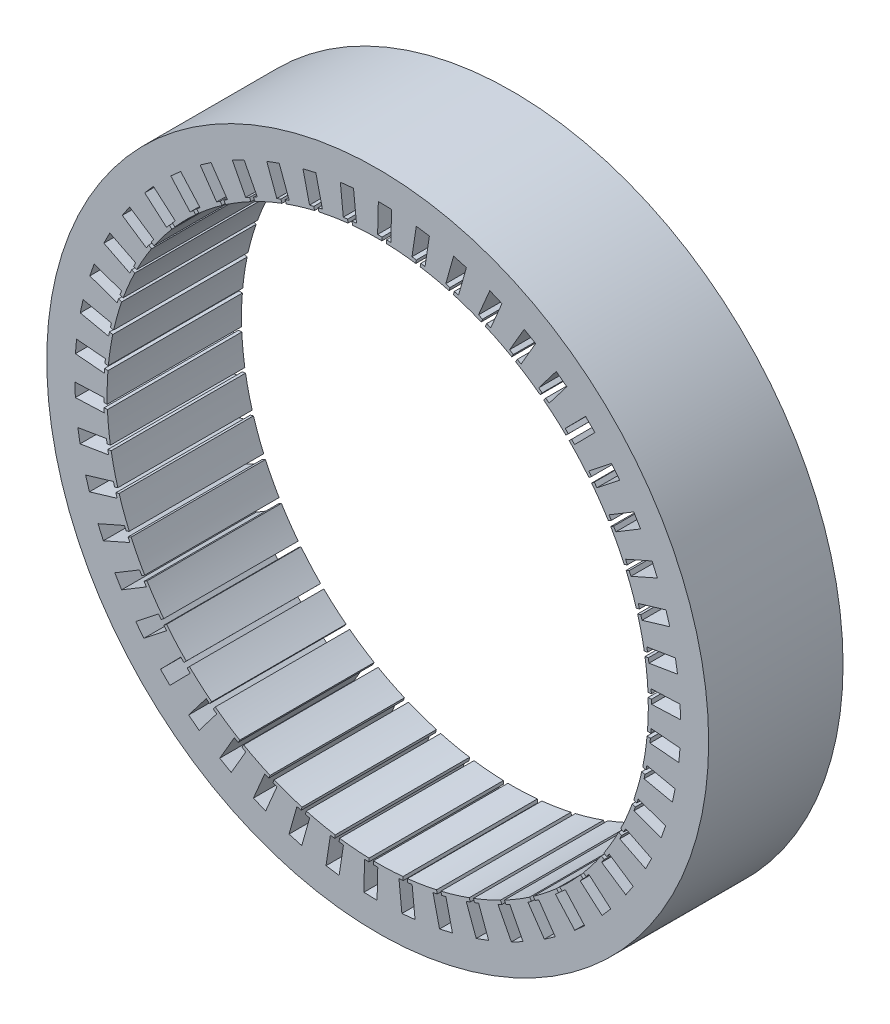
SolidWorks part; units mm, degrees
ref_plane "Спереди" through (0, 0, 0) normal (0, 0, 1) x (1, 0, 0)
ref_plane "Сверху" through (0, 0, 0) normal (0, 1, 0) x (1, 0, 0)
ref_plane "Справа" through (0, 0, 0) normal (1, 0, 0) x (0, 0, -1)
sketch "Эскиз1" plane through (0, 0, 0) normal (0, 0, 1) x (1, 0, 0)
  circle A0 centre (0, 0) radius 73.8769
  circle A1 centre (0, 0) radius 60.4
extrude "Rotor_stack" add sketch "Эскиз1" along normal blind 30 from offset 15
sketch "Эскиз2" plane through (0, 0, 0) normal (0, 0, 1) x (1, 0, 0)
  line L0 (59.5722, 1.8215) -> (61.1116, 1.8815)
  line L1 (61.1116, 1.8815) -> (61.1496, 0.9053)
  line L2 (61.1496, 0.9053) -> (67.6062, 1.1569)
  line L3 (67.6062, 1.1569) -> (67.4912, 4.1085)
  line L4 (67.4912, 4.1085) -> (61.0346, 3.8569)
  line L5 (61.0346, 3.8569) -> (61.0726, 2.8807)
  line L6 (61.0726, 2.8807) -> (59.5332, 2.8207)
  line L7 (59.5332, 2.8207) -> (59.5722, 1.8215)
  line L8 (58.8741, 9.2735) -> (60.3939, 9.5259)
  line L9 (60.3939, 9.5259) -> (60.554, 8.5622)
  line L10 (60.554, 8.5622) -> (66.9281, 9.6211)
  line L11 (66.9281, 9.6211) -> (66.4441, 12.535)
  line L12 (66.4441, 12.535) -> (60.0699, 11.4761)
  line L13 (60.0699, 11.4761) -> (60.23, 10.5124)
  line L14 (60.23, 10.5124) -> (58.7102, 10.26)
  line L15 (58.7102, 10.26) -> (58.8741, 9.2735)
  line L16 (57.2476, 16.5792) -> (58.7237, 17.0202)
  line L17 (58.7237, 17.0202) -> (59.0033, 16.0841)
  line L18 (59.0033, 16.0841) -> (65.1945, 17.9336)
  line L19 (65.1945, 17.9336) -> (64.3491, 20.7638)
  line L20 (64.3491, 20.7638) -> (58.1579, 18.9144)
  line L21 (58.1579, 18.9144) -> (58.4375, 17.9783)
  line L22 (58.4375, 17.9783) -> (56.9614, 17.5374)
  line L23 (56.9614, 17.5374) -> (57.2476, 16.5792)
  line L24 (54.7183, 23.6235) -> (56.1275, 24.246)
  line L25 (56.1275, 24.246) -> (56.5222, 23.3524)
  line L26 (56.5222, 23.3524) -> (62.4328, 25.9632)
  line L27 (62.4328, 25.9632) -> (61.2393, 28.6652)
  line L28 (61.2393, 28.6652) -> (55.3287, 26.0544)
  line L29 (55.3287, 26.0544) -> (55.7234, 25.1607)
  line L30 (55.7234, 25.1607) -> (54.3142, 24.5383)
  line L31 (54.3142, 24.5383) -> (54.7183, 23.6235)
  line L32 (51.326, 30.2953) -> (52.6461, 31.0895)
  line L33 (52.6461, 31.0895) -> (53.1497, 30.2524)
  line L34 (53.1497, 30.2524) -> (58.6864, 33.5834)
  line L35 (58.6864, 33.5834) -> (57.1637, 36.1145)
  line L36 (57.1637, 36.1145) -> (51.6269, 32.7834)
  line L37 (51.6269, 32.7834) -> (52.1305, 31.9463)
  line L38 (52.1305, 31.9463) -> (50.8105, 31.1522)
  line L39 (50.8105, 31.1522) -> (51.326, 30.2953)
  line L40 (47.1243, 36.4892) -> (48.3344, 37.4426)
  line L41 (48.3344, 37.4426) -> (48.9389, 36.6752)
  line L42 (48.9389, 36.6752) -> (54.0146, 40.6739)
  line L43 (54.0146, 40.6739) -> (52.1866, 42.9942)
  line L44 (52.1866, 42.9942) -> (47.111, 38.9955)
  line L45 (47.111, 38.9955) -> (47.7155, 38.2281)
  line L46 (47.7155, 38.2281) -> (46.5054, 37.2748)
  line L47 (46.5054, 37.2748) -> (47.1243, 36.4892)
  line L48 (42.1794, 42.1077) -> (43.2604, 43.2053)
  line L49 (43.2604, 43.2053) -> (43.9564, 42.5197)
  line L50 (43.9564, 42.5197) -> (48.4908, 47.123)
  line L51 (48.4908, 47.123) -> (46.3865, 49.1959)
  line L52 (46.3865, 49.1959) -> (41.8521, 44.5926)
  line L53 (41.8521, 44.5926) -> (42.548, 43.907)
  line L54 (42.548, 43.907) -> (41.4669, 42.8095)
  line L55 (41.4669, 42.8095) -> (42.1794, 42.1077)
  line L56 (36.5693, 47.0622) -> (37.5043, 48.2866)
  line L57 (37.5043, 48.2866) -> (38.2807, 47.6936)
  line L58 (38.2807, 47.6936) -> (42.2024, 52.829)
  line L59 (42.2024, 52.829) -> (39.8548, 54.6217)
  line L60 (39.8548, 54.6217) -> (35.9331, 49.4864)
  line L61 (35.9331, 49.4864) -> (36.7095, 48.8935)
  line L62 (36.7095, 48.8935) -> (35.7745, 47.6691)
  line L63 (35.7745, 47.6691) -> (36.5693, 47.0622)
  line L64 (30.3824, 51.2744) -> (31.1566, 52.6063)
  line L65 (31.1566, 52.6063) -> (32.0012, 52.1154)
  line L66 (32.0012, 52.1154) -> (35.2484, 57.7018)
  line L67 (35.2484, 57.7018) -> (32.6946, 59.1862)
  line L68 (32.6946, 59.1862) -> (29.4475, 53.5998)
  line L69 (29.4475, 53.5998) -> (30.2921, 53.1089)
  line L70 (30.2921, 53.1089) -> (29.5179, 51.777)
  line L71 (29.5179, 51.777) -> (30.3824, 51.2744)
  line L72 (23.7165, 54.678) -> (24.3176, 56.0965)
  line L73 (24.3176, 56.0965) -> (25.2171, 55.7153)
  line L74 (25.2171, 55.7153) -> (27.7385, 61.6645)
  line L75 (27.7385, 61.6645) -> (25.0188, 62.8172)
  line L76 (25.0188, 62.8172) -> (22.4974, 56.8679)
  line L77 (22.4974, 56.8679) -> (23.3969, 56.4867)
  line L78 (23.3969, 56.4867) -> (22.7958, 55.0683)
  line L79 (22.7958, 55.0683) -> (23.7165, 54.678)
  line L80 (16.6765, 57.2194) -> (17.0951, 58.7019)
  line L81 (17.0951, 58.7019) -> (18.0353, 58.4365)
  line L82 (18.0353, 58.4365) -> (19.7912, 64.6549)
  line L83 (19.7912, 64.6549) -> (16.9485, 65.4575)
  line L84 (16.9485, 65.4575) -> (15.1926, 59.2392)
  line L85 (15.1926, 59.2392) -> (16.1328, 58.9737)
  line L86 (16.1328, 58.9737) -> (15.7141, 57.4911)
  line L87 (15.7141, 57.4911) -> (16.6765, 57.2194)
  line L88 (9.3735, 58.8583) -> (9.603, 60.3816)
  line L89 (9.603, 60.3816) -> (10.569, 60.2361)
  line L90 (10.569, 60.2361) -> (11.5317, 66.6255)
  line L91 (11.5317, 66.6255) -> (8.6108, 67.0656)
  line L92 (8.6108, 67.0656) -> (7.6482, 60.6762)
  line L93 (7.6482, 60.6762) -> (8.6142, 60.5306)
  line L94 (8.6142, 60.5306) -> (8.3847, 59.0073)
  line L95 (8.3847, 59.0073) -> (9.3735, 58.8583)
  line L96 (1.9227, 59.569) -> (1.9595, 61.1091)
  line L97 (1.9595, 61.1091) -> (2.9361, 61.0858)
  line L98 (2.9361, 61.0858) -> (3.0904, 67.5455)
  line L99 (3.0904, 67.5455) -> (0.1374, 67.616)
  line L100 (0.1374, 67.616) -> (-0.0169, 61.1563)
  line L101 (-0.0169, 61.1563) -> (0.9598, 61.133)
  line L102 (0.9598, 61.133) -> (0.923, 59.5929)
  line L103 (0.923, 59.5929) -> (1.9227, 59.569)
  line L104 (-5.5584, 59.3402) -> (-5.715, 60.8728)
  line L105 (-5.715, 60.8728) -> (-4.7431, 60.9721)
  line L106 (-4.7431, 60.9721) -> (-5.3997, 67.4002)
  line L107 (-5.3997, 67.4002) -> (-8.3382, 67.1)
  line L108 (-8.3382, 67.1) -> (-7.6817, 60.6719)
  line L109 (-7.6817, 60.6719) -> (-6.7098, 60.7712)
  line L110 (-6.7098, 60.7712) -> (-6.5533, 59.2386)
  line L111 (-6.5533, 59.2386) -> (-5.5584, 59.3402)
  line L112 (-12.9519, 58.1757) -> (-13.2993, 59.6765)
  line L113 (-13.2993, 59.6765) -> (-12.3475, 59.8968)
  line L114 (-12.3475, 59.8968) -> (-13.8046, 66.192)
  line L115 (-13.8046, 66.192) -> (-16.6824, 65.5259)
  line L116 (-16.6824, 65.5259) -> (-15.2253, 59.2308)
  line L117 (-15.2253, 59.2308) -> (-14.2736, 59.451)
  line L118 (-14.2736, 59.451) -> (-13.9262, 57.9502)
  line L119 (-13.9262, 57.9502) -> (-12.9519, 58.1757)
  line L120 (-20.1411, 56.0936) -> (-20.6739, 57.5391)
  line L121 (-20.6739, 57.5391) -> (-19.7572, 57.877)
  line L122 (-19.7572, 57.877) -> (-21.9918, 63.9398)
  line L123 (-21.9918, 63.9398) -> (-24.7634, 62.9183)
  line L124 (-24.7634, 62.9183) -> (-22.5288, 56.8555)
  line L125 (-22.5288, 56.8555) -> (-21.6122, 57.1933)
  line L126 (-21.6122, 57.1933) -> (-21.0794, 55.7478)
  line L127 (-21.0794, 55.7478) -> (-20.1411, 56.0936)
  line L128 (-27.0127, 53.127) -> (-27.7224, 54.4943)
  line L129 (-27.7224, 54.4943) -> (-26.8554, 54.9444)
  line L130 (-26.8554, 54.9444) -> (-29.8322, 60.6793)
  line L131 (-29.8322, 60.6793) -> (-32.4539, 59.3185)
  line L132 (-32.4539, 59.3185) -> (-29.4771, 53.5835)
  line L133 (-29.4771, 53.5835) -> (-28.61, 54.0336)
  line L134 (-28.61, 54.0336) -> (-27.9003, 52.6663)
  line L135 (-27.9003, 52.6663) -> (-27.0127, 53.127)
  line L136 (-33.4583, 49.3224) -> (-34.3338, 50.59)
  line L137 (-34.3338, 50.59) -> (-33.53, 51.1452)
  line L138 (-33.53, 51.1452) -> (-37.2021, 56.4619)
  line L139 (-37.2021, 56.4619) -> (-39.6325, 54.7832)
  line L140 (-39.6325, 54.7832) -> (-35.9604, 49.4666)
  line L141 (-35.9604, 49.4666) -> (-35.1566, 50.0217)
  line L142 (-35.1566, 50.0217) -> (-34.2811, 48.7541)
  line L143 (-34.2811, 48.7541) -> (-33.4583, 49.3224)
  line L144 (-39.3762, 44.7401) -> (-40.4037, 45.888)
  line L145 (-40.4037, 45.888) -> (-39.6758, 46.5395)
  line L146 (-39.6758, 46.5395) -> (-43.9853, 51.354)
  line L147 (-43.9853, 51.354) -> (-46.1862, 49.384)
  line L148 (-46.1862, 49.384) -> (-41.8767, 44.5695)
  line L149 (-41.8767, 44.5695) -> (-41.1488, 45.221)
  line L150 (-41.1488, 45.221) -> (-40.1213, 44.0731)
  line L151 (-40.1213, 44.0731) -> (-39.3762, 44.7401)
  line L152 (-44.6731, 39.4522) -> (-45.8364, 40.4622)
  line L153 (-45.8364, 40.4622) -> (-45.1959, 41.1999)
  line L154 (-45.1959, 41.1999) -> (-50.0748, 45.4363)
  line L155 (-50.0748, 45.4363) -> (-52.0115, 43.2059)
  line L156 (-52.0115, 43.2059) -> (-47.1325, 38.9695)
  line L157 (-47.1325, 38.9695) -> (-46.492, 39.7071)
  line L158 (-46.492, 39.7071) -> (-45.3288, 38.6971)
  line L159 (-45.3288, 38.6971) -> (-44.6731, 39.4522)
  line L160 (-49.2655, 33.542) -> (-50.5462, 34.3983)
  line L161 (-50.5462, 34.3983) -> (-50.0032, 35.2104)
  line L162 (-50.0032, 35.2104) -> (-55.3746, 38.802)
  line L163 (-55.3746, 38.802) -> (-57.0165, 36.3464)
  line L164 (-57.0165, 36.3464) -> (-51.645, 32.7549)
  line L165 (-51.645, 32.7549) -> (-51.102, 33.567)
  line L166 (-51.102, 33.567) -> (-49.8214, 32.7107)
  line L167 (-49.8214, 32.7107) -> (-49.2655, 33.542)
  line L168 (-53.081, 27.1029) -> (-54.4589, 27.792)
  line L169 (-54.4589, 27.792) -> (-54.0219, 28.6657)
  line L170 (-54.0219, 28.6657) -> (-59.8012, 31.5557)
  line L171 (-59.8012, 31.5557) -> (-61.1223, 28.9138)
  line L172 (-61.1223, 28.9138) -> (-55.3431, 26.0238)
  line L173 (-55.3431, 26.0238) -> (-54.9061, 26.8976)
  line L174 (-54.9061, 26.8976) -> (-53.5282, 26.2085)
  line L175 (-53.5282, 26.2085) -> (-53.081, 27.1029)
  line L176 (-56.0593, 20.2364) -> (-57.5127, 20.7473)
  line L177 (-57.5127, 20.7473) -> (-57.1887, 21.669)
  line L178 (-57.1887, 21.669) -> (-63.2846, 23.8118)
  line L179 (-63.2846, 23.8118) -> (-64.2642, 21.0251)
  line L180 (-64.2642, 21.0251) -> (-58.1683, 18.8823)
  line L181 (-58.1683, 18.8823) -> (-57.8443, 19.8039)
  line L182 (-57.8443, 19.8039) -> (-56.391, 19.293)
  line L183 (-56.391, 19.293) -> (-56.0593, 20.2364)
  line L184 (-58.1536, 13.0507) -> (-59.6595, 13.3755)
  line L185 (-59.6595, 13.3755) -> (-59.4536, 14.3304)
  line L186 (-59.4536, 14.3304) -> (-65.77, 15.6924)
  line L187 (-65.77, 15.6924) -> (-66.3926, 12.8049)
  line L188 (-66.3926, 12.8049) -> (-60.0762, 11.443)
  line L189 (-60.0762, 11.443) -> (-59.8703, 12.3979)
  line L190 (-59.8703, 12.3979) -> (-58.3644, 12.0732)
  line L191 (-58.3644, 12.0732) -> (-58.1536, 13.0507)
  line L192 (-59.3307, 5.6593) -> (-60.8655, 5.7927)
  line L193 (-60.8655, 5.7927) -> (-60.7809, 6.7659)
  line L194 (-60.7809, 6.7659) -> (-67.2181, 7.3255)
  line L195 (-67.2181, 7.3255) -> (-67.4739, 4.3827)
  line L196 (-67.4739, 4.3827) -> (-61.0367, 3.8232)
  line L197 (-61.0367, 3.8232) -> (-60.9521, 4.7964)
  line L198 (-60.9521, 4.7964) -> (-59.4173, 4.663)
  line L199 (-59.4173, 4.663) -> (-59.3307, 5.6593)
  line L200 (-59.5722, -1.8215) -> (-61.1116, -1.8815)
  line L201 (-61.1116, -1.8815) -> (-61.1496, -0.9053)
  line L202 (-61.1496, -0.9053) -> (-67.6062, -1.1569)
  line L203 (-67.6062, -1.1569) -> (-67.4912, -4.1085)
  line L204 (-67.4912, -4.1085) -> (-61.0346, -3.8569)
  line L205 (-61.0346, -3.8569) -> (-61.0726, -2.8807)
  line L206 (-61.0726, -2.8807) -> (-59.5332, -2.8207)
  line L207 (-59.5332, -2.8207) -> (-59.5722, -1.8215)
  line L208 (-58.8741, -9.2735) -> (-60.3939, -9.5259)
  line L209 (-60.3939, -9.5259) -> (-60.554, -8.5622)
  line L210 (-60.554, -8.5622) -> (-66.9281, -9.6211)
  line L211 (-66.9281, -9.6211) -> (-66.4441, -12.535)
  line L212 (-66.4441, -12.535) -> (-60.0699, -11.4761)
  line L213 (-60.0699, -11.4761) -> (-60.23, -10.5124)
  line L214 (-60.23, -10.5124) -> (-58.7102, -10.26)
  line L215 (-58.7102, -10.26) -> (-58.8741, -9.2735)
  line L216 (-57.2476, -16.5792) -> (-58.7237, -17.0202)
  line L217 (-58.7237, -17.0202) -> (-59.0033, -16.0841)
  line L218 (-59.0033, -16.0841) -> (-65.1945, -17.9336)
  line L219 (-65.1945, -17.9336) -> (-64.3491, -20.7638)
  line L220 (-64.3491, -20.7638) -> (-58.1579, -18.9144)
  line L221 (-58.1579, -18.9144) -> (-58.4375, -17.9783)
  line L222 (-58.4375, -17.9783) -> (-56.9614, -17.5374)
  line L223 (-56.9614, -17.5374) -> (-57.2476, -16.5792)
  line L224 (-54.7183, -23.6235) -> (-56.1275, -24.246)
  line L225 (-56.1275, -24.246) -> (-56.5222, -23.3524)
  line L226 (-56.5222, -23.3524) -> (-62.4328, -25.9632)
  line L227 (-62.4328, -25.9632) -> (-61.2393, -28.6652)
  line L228 (-61.2393, -28.6652) -> (-55.3287, -26.0544)
  line L229 (-55.3287, -26.0544) -> (-55.7234, -25.1607)
  line L230 (-55.7234, -25.1607) -> (-54.3142, -24.5383)
  line L231 (-54.3142, -24.5383) -> (-54.7183, -23.6235)
  line L232 (-51.326, -30.2953) -> (-52.6461, -31.0895)
  line L233 (-52.6461, -31.0895) -> (-53.1497, -30.2524)
  line L234 (-53.1497, -30.2524) -> (-58.6864, -33.5834)
  line L235 (-58.6864, -33.5834) -> (-57.1637, -36.1145)
  line L236 (-57.1637, -36.1145) -> (-51.6269, -32.7834)
  line L237 (-51.6269, -32.7834) -> (-52.1305, -31.9463)
  line L238 (-52.1305, -31.9463) -> (-50.8105, -31.1522)
  line L239 (-50.8105, -31.1522) -> (-51.326, -30.2953)
  line L240 (-47.1243, -36.4892) -> (-48.3344, -37.4426)
  line L241 (-48.3344, -37.4426) -> (-48.9389, -36.6752)
  line L242 (-48.9389, -36.6752) -> (-54.0146, -40.6739)
  line L243 (-54.0146, -40.6739) -> (-52.1866, -42.9942)
  line L244 (-52.1866, -42.9942) -> (-47.111, -38.9955)
  line L245 (-47.111, -38.9955) -> (-47.7155, -38.2281)
  line L246 (-47.7155, -38.2281) -> (-46.5054, -37.2748)
  line L247 (-46.5054, -37.2748) -> (-47.1243, -36.4892)
  line L248 (-42.1794, -42.1077) -> (-43.2604, -43.2053)
  line L249 (-43.2604, -43.2053) -> (-43.9564, -42.5197)
  line L250 (-43.9564, -42.5197) -> (-48.4908, -47.123)
  line L251 (-48.4908, -47.123) -> (-46.3865, -49.1959)
  line L252 (-46.3865, -49.1959) -> (-41.8521, -44.5926)
  line L253 (-41.8521, -44.5926) -> (-42.548, -43.907)
  line L254 (-42.548, -43.907) -> (-41.4669, -42.8095)
  line L255 (-41.4669, -42.8095) -> (-42.1794, -42.1077)
  line L256 (-36.5693, -47.0622) -> (-37.5043, -48.2866)
  line L257 (-37.5043, -48.2866) -> (-38.2807, -47.6936)
  line L258 (-38.2807, -47.6936) -> (-42.2024, -52.829)
  line L259 (-42.2024, -52.829) -> (-39.8548, -54.6217)
  line L260 (-39.8548, -54.6217) -> (-35.9331, -49.4864)
  line L261 (-35.9331, -49.4864) -> (-36.7095, -48.8935)
  line L262 (-36.7095, -48.8935) -> (-35.7745, -47.6691)
  line L263 (-35.7745, -47.6691) -> (-36.5693, -47.0622)
  line L264 (-30.3824, -51.2744) -> (-31.1566, -52.6063)
  line L265 (-31.1566, -52.6063) -> (-32.0012, -52.1154)
  line L266 (-32.0012, -52.1154) -> (-35.2484, -57.7018)
  line L267 (-35.2484, -57.7018) -> (-32.6946, -59.1862)
  line L268 (-32.6946, -59.1862) -> (-29.4475, -53.5998)
  line L269 (-29.4475, -53.5998) -> (-30.2921, -53.1089)
  line L270 (-30.2921, -53.1089) -> (-29.5179, -51.777)
  line L271 (-29.5179, -51.777) -> (-30.3824, -51.2744)
  line L272 (-23.7165, -54.678) -> (-24.3176, -56.0965)
  line L273 (-24.3176, -56.0965) -> (-25.2171, -55.7153)
  line L274 (-25.2171, -55.7153) -> (-27.7385, -61.6645)
  line L275 (-27.7385, -61.6645) -> (-25.0188, -62.8172)
  line L276 (-25.0188, -62.8172) -> (-22.4974, -56.8679)
  line L277 (-22.4974, -56.8679) -> (-23.3969, -56.4867)
  line L278 (-23.3969, -56.4867) -> (-22.7958, -55.0683)
  line L279 (-22.7958, -55.0683) -> (-23.7165, -54.678)
  line L280 (-16.6765, -57.2194) -> (-17.0951, -58.7019)
  line L281 (-17.0951, -58.7019) -> (-18.0353, -58.4365)
  line L282 (-18.0353, -58.4365) -> (-19.7912, -64.6549)
  line L283 (-19.7912, -64.6549) -> (-16.9485, -65.4575)
  line L284 (-16.9485, -65.4575) -> (-15.1926, -59.2392)
  line L285 (-15.1926, -59.2392) -> (-16.1328, -58.9737)
  line L286 (-16.1328, -58.9737) -> (-15.7141, -57.4911)
  line L287 (-15.7141, -57.4911) -> (-16.6765, -57.2194)
  line L288 (-9.3735, -58.8583) -> (-9.603, -60.3816)
  line L289 (-9.603, -60.3816) -> (-10.569, -60.2361)
  line L290 (-10.569, -60.2361) -> (-11.5317, -66.6255)
  line L291 (-11.5317, -66.6255) -> (-8.6108, -67.0656)
  line L292 (-8.6108, -67.0656) -> (-7.6482, -60.6762)
  line L293 (-7.6482, -60.6762) -> (-8.6142, -60.5306)
  line L294 (-8.6142, -60.5306) -> (-8.3847, -59.0073)
  line L295 (-8.3847, -59.0073) -> (-9.3735, -58.8583)
  line L296 (-1.9227, -59.569) -> (-1.9595, -61.1091)
  line L297 (-1.9595, -61.1091) -> (-2.9361, -61.0858)
  line L298 (-2.9361, -61.0858) -> (-3.0904, -67.5455)
  line L299 (-3.0904, -67.5455) -> (-0.1374, -67.616)
  line L300 (-0.1374, -67.616) -> (0.0169, -61.1563)
  line L301 (0.0169, -61.1563) -> (-0.9598, -61.133)
  line L302 (-0.9598, -61.133) -> (-0.923, -59.5929)
  line L303 (-0.923, -59.5929) -> (-1.9227, -59.569)
  line L304 (5.5584, -59.3402) -> (5.715, -60.8728)
  line L305 (5.715, -60.8728) -> (4.7431, -60.9721)
  line L306 (4.7431, -60.9721) -> (5.3997, -67.4002)
  line L307 (5.3997, -67.4002) -> (8.3382, -67.1)
  line L308 (8.3382, -67.1) -> (7.6817, -60.6719)
  line L309 (7.6817, -60.6719) -> (6.7098, -60.7712)
  line L310 (6.7098, -60.7712) -> (6.5533, -59.2386)
  line L311 (6.5533, -59.2386) -> (5.5584, -59.3402)
  line L312 (12.9519, -58.1757) -> (13.2993, -59.6765)
  line L313 (13.2993, -59.6765) -> (12.3475, -59.8968)
  line L314 (12.3475, -59.8968) -> (13.8046, -66.192)
  line L315 (13.8046, -66.192) -> (16.6824, -65.5259)
  line L316 (16.6824, -65.5259) -> (15.2253, -59.2308)
  line L317 (15.2253, -59.2308) -> (14.2736, -59.451)
  line L318 (14.2736, -59.451) -> (13.9262, -57.9502)
  line L319 (13.9262, -57.9502) -> (12.9519, -58.1757)
  line L320 (20.1411, -56.0936) -> (20.6739, -57.5391)
  line L321 (20.6739, -57.5391) -> (19.7572, -57.877)
  line L322 (19.7572, -57.877) -> (21.9918, -63.9398)
  line L323 (21.9918, -63.9398) -> (24.7634, -62.9183)
  line L324 (24.7634, -62.9183) -> (22.5288, -56.8555)
  line L325 (22.5288, -56.8555) -> (21.6122, -57.1933)
  line L326 (21.6122, -57.1933) -> (21.0794, -55.7478)
  line L327 (21.0794, -55.7478) -> (20.1411, -56.0936)
  line L328 (27.0127, -53.127) -> (27.7224, -54.4943)
  line L329 (27.7224, -54.4943) -> (26.8554, -54.9444)
  line L330 (26.8554, -54.9444) -> (29.8322, -60.6793)
  line L331 (29.8322, -60.6793) -> (32.4539, -59.3185)
  line L332 (32.4539, -59.3185) -> (29.4771, -53.5835)
  line L333 (29.4771, -53.5835) -> (28.61, -54.0336)
  line L334 (28.61, -54.0336) -> (27.9003, -52.6663)
  line L335 (27.9003, -52.6663) -> (27.0127, -53.127)
  line L336 (33.4583, -49.3224) -> (34.3338, -50.59)
  line L337 (34.3338, -50.59) -> (33.53, -51.1452)
  line L338 (33.53, -51.1452) -> (37.2021, -56.4619)
  line L339 (37.2021, -56.4619) -> (39.6325, -54.7832)
  line L340 (39.6325, -54.7832) -> (35.9604, -49.4666)
  line L341 (35.9604, -49.4666) -> (35.1566, -50.0217)
  line L342 (35.1566, -50.0217) -> (34.2811, -48.7541)
  line L343 (34.2811, -48.7541) -> (33.4583, -49.3224)
  line L344 (39.3762, -44.7401) -> (40.4037, -45.888)
  line L345 (40.4037, -45.888) -> (39.6758, -46.5395)
  line L346 (39.6758, -46.5395) -> (43.9853, -51.354)
  line L347 (43.9853, -51.354) -> (46.1862, -49.384)
  line L348 (46.1862, -49.384) -> (41.8767, -44.5695)
  line L349 (41.8767, -44.5695) -> (41.1488, -45.221)
  line L350 (41.1488, -45.221) -> (40.1213, -44.0731)
  line L351 (40.1213, -44.0731) -> (39.3762, -44.7401)
  line L352 (44.6731, -39.4522) -> (45.8364, -40.4622)
  line L353 (45.8364, -40.4622) -> (45.1959, -41.1999)
  line L354 (45.1959, -41.1999) -> (50.0748, -45.4363)
  line L355 (50.0748, -45.4363) -> (52.0115, -43.2059)
  line L356 (52.0115, -43.2059) -> (47.1325, -38.9695)
  line L357 (47.1325, -38.9695) -> (46.492, -39.7071)
  line L358 (46.492, -39.7071) -> (45.3288, -38.6971)
  line L359 (45.3288, -38.6971) -> (44.6731, -39.4522)
  line L360 (49.2655, -33.542) -> (50.5462, -34.3983)
  line L361 (50.5462, -34.3983) -> (50.0032, -35.2104)
  line L362 (50.0032, -35.2104) -> (55.3746, -38.802)
  line L363 (55.3746, -38.802) -> (57.0165, -36.3464)
  line L364 (57.0165, -36.3464) -> (51.645, -32.7549)
  line L365 (51.645, -32.7549) -> (51.102, -33.567)
  line L366 (51.102, -33.567) -> (49.8214, -32.7107)
  line L367 (49.8214, -32.7107) -> (49.2655, -33.542)
  line L368 (53.081, -27.1029) -> (54.4589, -27.792)
  line L369 (54.4589, -27.792) -> (54.0219, -28.6657)
  line L370 (54.0219, -28.6657) -> (59.8012, -31.5557)
  line L371 (59.8012, -31.5557) -> (61.1223, -28.9138)
  line L372 (61.1223, -28.9138) -> (55.3431, -26.0238)
  line L373 (55.3431, -26.0238) -> (54.9061, -26.8976)
  line L374 (54.9061, -26.8976) -> (53.5282, -26.2085)
  line L375 (53.5282, -26.2085) -> (53.081, -27.1029)
  line L376 (56.0593, -20.2364) -> (57.5127, -20.7473)
  line L377 (57.5127, -20.7473) -> (57.1887, -21.669)
  line L378 (57.1887, -21.669) -> (63.2846, -23.8118)
  line L379 (63.2846, -23.8118) -> (64.2642, -21.0251)
  line L380 (64.2642, -21.0251) -> (58.1683, -18.8823)
  line L381 (58.1683, -18.8823) -> (57.8443, -19.8039)
  line L382 (57.8443, -19.8039) -> (56.391, -19.293)
  line L383 (56.391, -19.293) -> (56.0593, -20.2364)
  line L384 (58.1536, -13.0507) -> (59.6595, -13.3755)
  line L385 (59.6595, -13.3755) -> (59.4536, -14.3304)
  line L386 (59.4536, -14.3304) -> (65.77, -15.6924)
  line L387 (65.77, -15.6924) -> (66.3926, -12.8049)
  line L388 (66.3926, -12.8049) -> (60.0762, -11.443)
  line L389 (60.0762, -11.443) -> (59.8703, -12.3979)
  line L390 (59.8703, -12.3979) -> (58.3644, -12.0732)
  line L391 (58.3644, -12.0732) -> (58.1536, -13.0507)
  line L392 (59.3307, -5.6593) -> (60.8655, -5.7927)
  line L393 (60.8655, -5.7927) -> (60.7809, -6.7659)
  line L394 (60.7809, -6.7659) -> (67.2181, -7.3255)
  line L395 (67.2181, -7.3255) -> (67.4739, -4.3827)
  line L396 (67.4739, -4.3827) -> (61.0367, -3.8232)
  line L397 (61.0367, -3.8232) -> (60.9521, -4.7964)
  line L398 (60.9521, -4.7964) -> (59.4173, -4.663)
  line L399 (59.4173, -4.663) -> (59.3307, -5.6593)
extrude "Rotor_50_slots" cut sketch "Эскиз2" against normal mid plane 32
